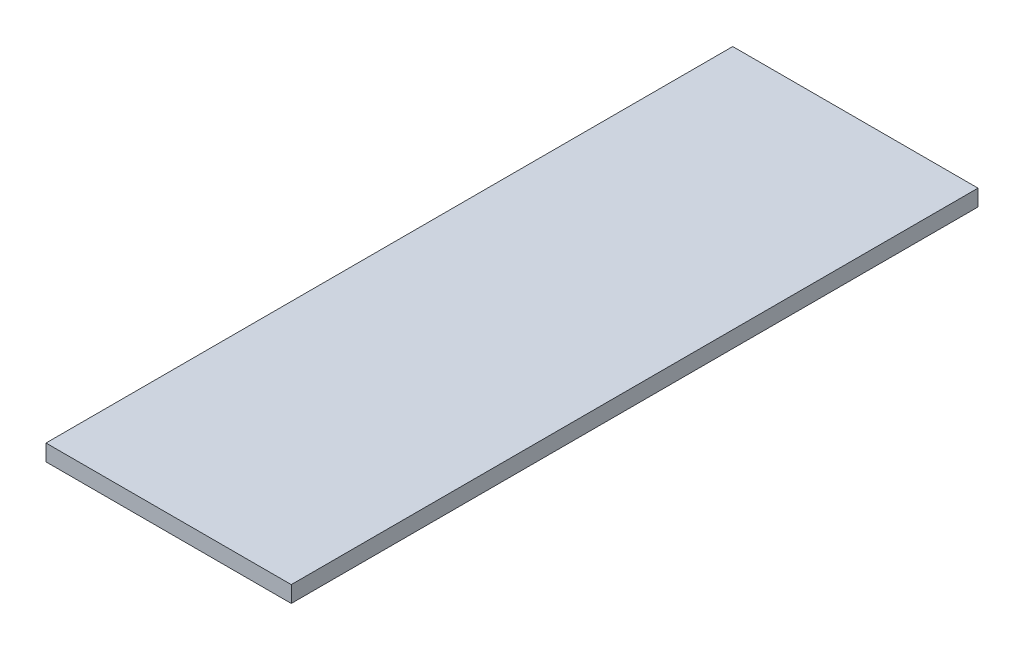
SolidWorks part; units mm, degrees
ref_plane "Front Plane" through (0, 0, 0) normal (0, 0, 1) x (1, 0, 0)
ref_plane "Top Plane" through (0, 0, 0) normal (0, 1, 0) x (1, 0, 0)
ref_plane "Right Plane" through (0, 0, 0) normal (1, 0, 0) x (0, 0, -1)
sketch "Sketch1" plane through (0, 0, 0) normal (0, 1, 0) x (1, 0, 0)
  line L1 (0, 0) -> (75, 0)
  line L2 (0, 0) -> (0, 210)
  line L3 (0, 210) -> (75, 210)
  line L4 (75, 0) -> (75, 210)
  dimension "D1" = 210
  dimension "D2" = 75
extrude "Boss-Extrude1" add sketch "Sketch1" along normal blind 5
